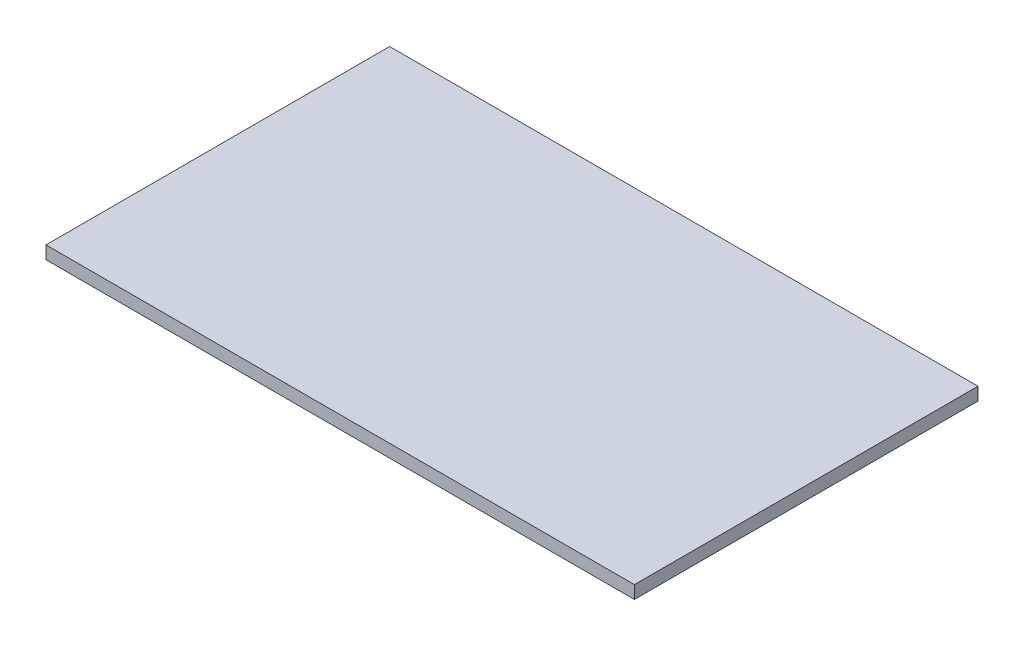
SolidWorks part; units mm, degrees
ref_plane "Front Plane" through (0, 0, 0) normal (0, 0, 1) x (1, 0, 0)
ref_plane "Top Plane" through (0, 0, 0) normal (0, 1, 0) x (1, 0, 0)
ref_plane "Right Plane" through (0, 0, 0) normal (1, 0, 0) x (0, 0, -1)
sketch "Sketch1" plane through (0, 0, 0) normal (0, 1, 0) x (1, 0, 0)
  line L1 (-98.5616, 82.4003) -> (38.4384, 82.4003)
  line L2 (-98.5616, 82.4003) -> (-98.5616, 2.4003)
  line L3 (-98.5616, 2.4003) -> (38.4384, 2.4003)
  line L4 (38.4384, 82.4003) -> (38.4384, 2.4003)
  dimension "D1" = 137
  dimension "D2" = 80
extrude "Boss-Extrude1" add sketch "Sketch1" along normal blind 3
